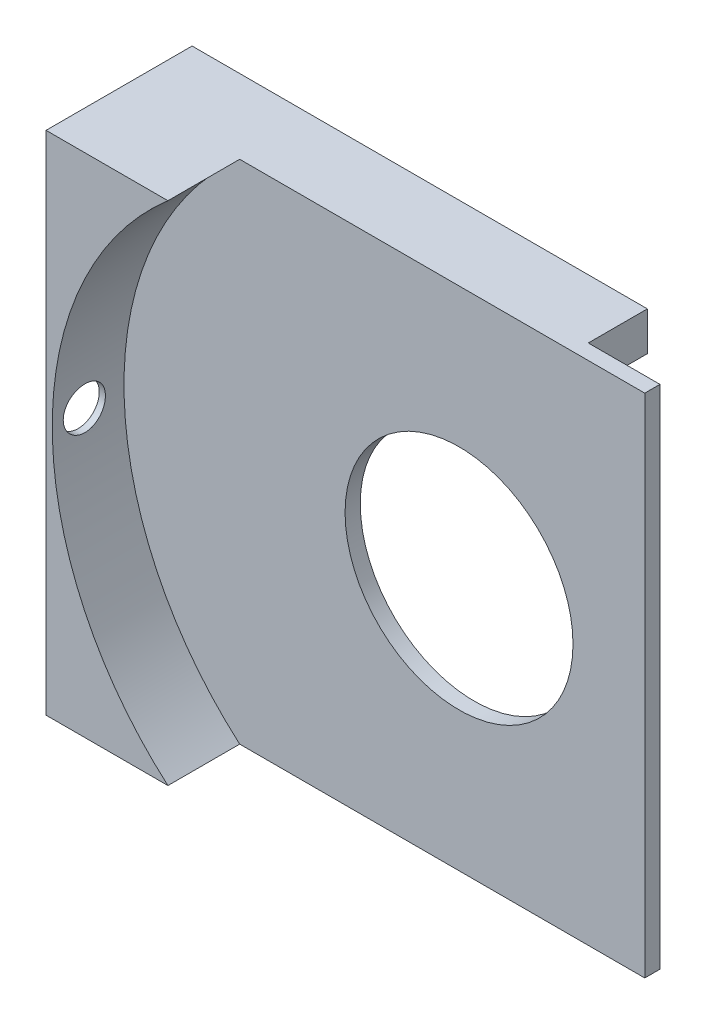
SolidWorks part; units mm, degrees
ref_plane "Front Plane" through (0, 0, 0) normal (0, 0, 1) x (1, 0, 0)
ref_plane "Top Plane" through (0, 0, 0) normal (0, 1, 0) x (1, 0, 0)
ref_plane "Right Plane" through (0, 0, 0) normal (1, 0, 0) x (0, 0, -1)
sketch "Sketch1" plane through (0, 0, 0) normal (0, 0, 1) x (1, 0, 0)
  line L1 (-24.9265, 30.0943) -> (37.4943, 30.0943)
  line L2 (-24.9265, 30.0943) -> (-24.9265, -29.9057)
  line L3 (-24.9265, -29.9057) -> (37.4943, -29.9057)
  line L4 (37.4943, 30.0943) -> (37.4943, -29.9057)
  line L5 (-23.9265, -4.499) -> (-23.9265, 4.6875) construction
  circle A0 centre (15.4943, 0.0943) radius 13.5
  circle A2 centre (15.4943, 0.0943) radius 13.1445 construction
  point P7 (37.4943, 0.0943)
  dimension "D1" = 27
  dimension "D2" = 60
  dimension "D3" = 22
  dimension "D4" = 1
extrude "Boss-Extrude1" add sketch "Sketch1" along normal blind 1.8 contours A0 L4 L1 L2 L3
sketch "Sketch2" plane through (0, 0, 1.8) normal (0, 0, 1) x (1, 0, 0)
  line L1 (-24.9265, -29.9057) -> (29.0043, -29.9057)
  line L2 (-24.9265, -29.9057) -> (-24.9265, -25.3057)
  line L3 (-24.9265, 30.0943) -> (37.4943, 30.0943) construction
  line L4 (29.0043, -29.9057) -> (29.0043, -25.3057)
  line L5 (-24.9265, 30.0943) -> (-24.9265, -29.9057) construction
  line L6 (29.0043, 30.0943) -> (-24.9265, 30.0943)
  line L7 (29.0043, 30.0943) -> (29.0043, 25.4943)
  line L8 (32.0043, 22.3193) -> (32.0043, -22.1307) construction
  line L9 (-24.9265, 30.0943) -> (-24.9265, 25.4943)
  line L10 (29.0043, -29.9057) -> (-24.9265, -29.9057)
  line L11 (-28.3207, 25.4943) -> (28.8293, 25.4943) construction
  line L12 (28.8293, -25.3057) -> (-28.3207, -25.3057) construction
  line L13 (29.0043, -29.9057) -> (29.0043, -25.3057)
  line L14 (29.0043, -25.3057) -> (-24.9265, -25.3057)
  line L15 (-24.9265, -29.9057) -> (-24.9265, -25.3057)
  line L16 (29.0043, 30.0943) -> (-24.9265, 30.0943)
  line L17 (29.0043, 30.0943) -> (29.0043, 25.4943)
  line L18 (29.0043, 25.4943) -> (-24.9265, 25.4943)
  line L19 (-24.9265, 30.0943) -> (-24.9265, 25.4943)
  line L28 (29.0043, 30.0943) -> (22.0043, 30.0943)
  line L29 (29.0043, 30.0943) -> (29.0043, 25.4943)
  line L30 (29.0043, 25.4943) -> (22.0043, 25.4943)
  line L31 (22.0043, 30.0943) -> (22.0043, 25.4943)
  line L33 (29.0043, -29.9057) -> (22.0043, -29.9057)
  line L34 (29.0043, -29.9057) -> (29.0043, -25.3057)
  line L35 (29.0043, -25.3057) -> (22.0043, -25.3057)
  line L36 (22.0043, -29.9057) -> (22.0043, -25.3057)
  line L38 (-24.9265, -29.9057) -> (-17.9265, -29.9057)
  line L39 (-24.9265, -29.9057) -> (-24.9265, -25.3057)
  line L40 (-24.9265, -25.3057) -> (-17.9265, -25.3057)
  line L41 (-17.9265, -29.9057) -> (-17.9265, -25.3057)
  line L42 (-24.9265, 30.0943) -> (-17.9265, 30.0943)
  line L43 (-24.9265, 30.0943) -> (-24.9265, 25.4943)
  line L44 (-24.9265, 25.4943) -> (-17.9265, 25.4943)
  line L45 (-17.9265, 30.0943) -> (-17.9265, 25.4943)
  dimension "D1" = 7
  dimension "D2" = 7
  dimension "D3" = 3
extrude "Boss-Extrude2" add sketch "Sketch2" against normal blind 7 from surface at -1.8 starting at face at (28.9943, 0.0943, 0)
sketch "Sketch3" plane through (0, 0, 1.8) normal (0, 0, 1) x (1, 0, 0)
  line L2 (-24.9265, 30.0943) -> (37.4943, 30.0943) construction
  line L3 (-24.9265, -29.9057) -> (37.4943, -29.9057) construction
  line L4 (-23.9265, -4.499) -> (-23.9265, 4.6875)
  line L5 (-10.4883, 30.0943) -> (-24.9265, 30.0943)
  line L6 (-24.9265, 30.0943) -> (-24.9265, -29.9057)
  line L7 (-24.9265, -29.9057) -> (-10.4883, -29.9057)
  arc A0 (-10.4883, 30.0943) -> (-10.4883, -29.9057) centre (15.4943, 0.0943) ccw
  arc A1 (-23.9265, -4.499) -> (-23.9265, 4.6875) centre (15.4943, 0.0943) ccw construction
  line M3 (37.4943, 30.0943) -> (-24.9265, 30.0943)
  line M4 (-24.9265, 30.0943) -> (-24.9265, -29.9057)
  line M5 (-24.9265, -29.9057) -> (37.4943, -29.9057)
extrude "Boss-Extrude3" add sketch "Sketch3" along normal blind 8.5 contours A0 M3 M4 M5
sketch "Sketch4" plane through (-24.9265, 0, 0) normal (-1, 0, 0) x (0, 0, 1)
  circle A0 centre (6.499, 0.0943) radius 2.5
  circle A1 centre (6.499, 0.0943) radius 2.0828 construction
  dimension "D1" = 5
extrude "Cut-Extrude1" cut sketch "Sketch4" against normal up to next
